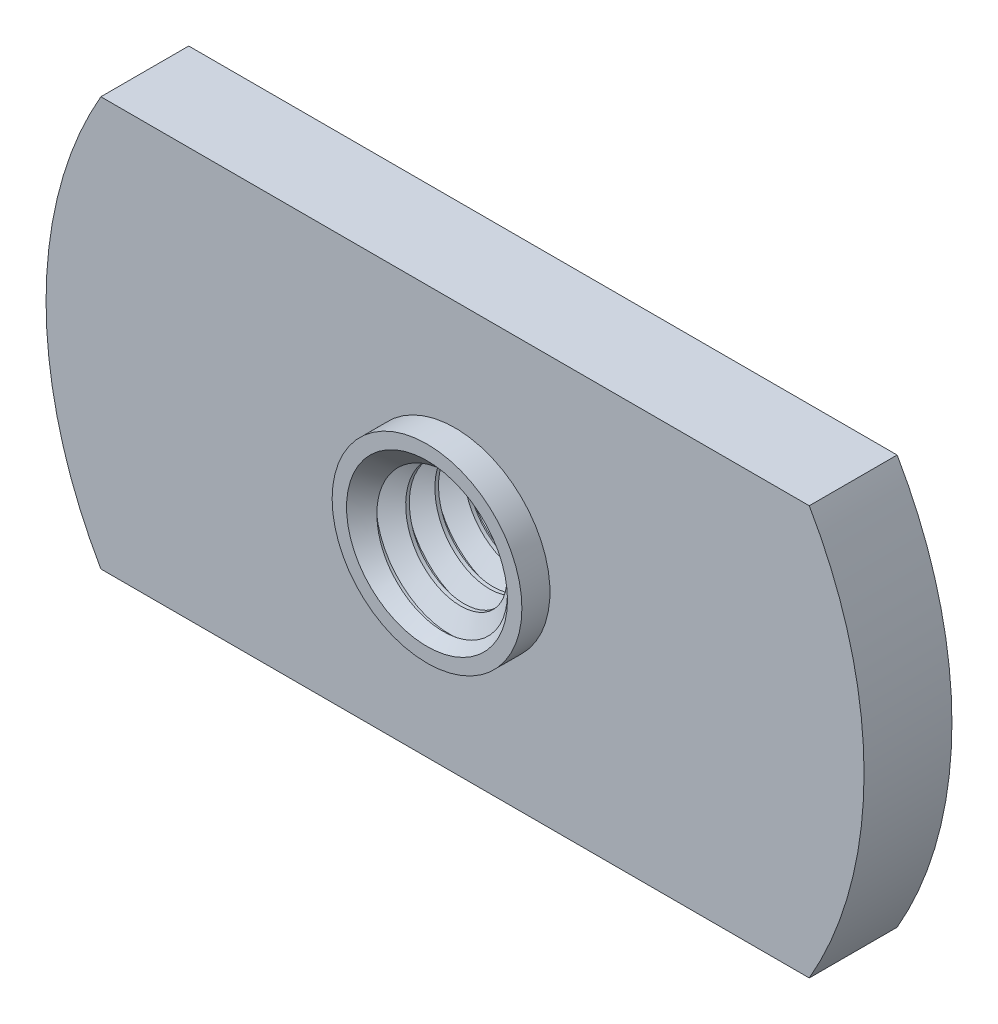
SolidWorks part; units mm, degrees
ref_plane "Front Plane" through (0, 0, 0) normal (0, 0, 1) x (1, 0, 0)
ref_plane "Top Plane" through (0, 0, 0) normal (0, 1, 0) x (1, 0, 0)
ref_plane "Right Plane" through (0, 0, 0) normal (1, 0, 0) x (0, 0, -1)
sketch "Sketch1" plane through (0, 0, 0) normal (0, 0, 1) x (1, 0, 0)
  line L0 (0, 5.5562) -> (0, -5.5562) construction
  line L1 (11.1125, 0) -> (-11.1125, 0) construction
  point P4 (0, 0)
  point P8 (0, 0)
  dimension "Length" = 22.225
  dimension "Width" = 11.1125
sketch "Sketch2" plane through (0, 0, 0) normal (1, 0, 0) x (0, 0, -1)
  line L0 (0, 0) -> (2.3876, 0) construction
  line L1 (0, 0) -> (-0.762, 0) construction
  line L2 (-0.762, 2.5781) -> (-0.762, -2.5781) construction
  line L3 (2.3876, 2.0828) -> (2.3876, -2.0828) construction
  line L5 (2.3876, -2.0828) -> (1.5939, -2.0828) construction
  line L6 (0, 5.5562) -> (0, -5.5562) construction
  point P7 (-0.762, 0)
  point P10 (2.3876, 0)
  dimension "E" = 5.1562
  dimension "Thread Dia" = 4.1656
  dimension "Pitch" = 0.7937
  dimension "B" = 2.3876
  dimension "F" = 0.762
sketch "Sketch3" plane through (0, 0, 0) normal (0, 0, 1) x (1, 0, 0)
  line L0 (9.6237, -5.5562) -> (-9.6237, -5.5562)
  line L4 (9.6237, 5.5562) -> (-9.6237, 5.5562)
  arc A2 (9.6237, 5.5562) -> (9.6237, -5.5562) centre (0, 0) cw
  arc A3 (-9.6237, 5.5562) -> (-9.6237, -5.5562) centre (0, 0) ccw
  circle A4 centre (0, 0) radius 2.0828
  point P3 (0, -2.0828)
  point P6 (-11.1125, 0)
extrude "Boss-Extrude1" add sketch "Sketch3" against normal up to vertex (2.3876 mm away) up to point (0, 0, -2.3876)
sketch "Sketch4" plane through (0, 0, 0) normal (0, 0, 1) x (1, 0, 0)
  circle A0 centre (0, 0) radius 2.0828 construction
  circle A1 centre (0, 0) radius 2.0828
  circle A2 centre (0, 0) radius 2.5781
  point P4 (0, 2.5781)
extrude "Boss-Extrude2" add sketch "Sketch4" along normal up to vertex (0.762 mm away) up to point (0, 0, 0.762)
sketch "Sketch5" plane through (0, 0, 0.762) normal (0, 0, 1) x (1, 0, 0)
  circle A0 centre (0, 0) radius 2.1869
  dimension "D1" = 4.3739
extrude "Cut-Extrude1" cut sketch "Sketch5" against normal through all draft 45
sketch "Sketch6" plane through (0, 0, 0.762) normal (0, 0, 1) x (1, 0, 0)
  circle A1 centre (0, 0) radius 2.0828
  circle A2 centre (0, 0) radius 2.0828 construction
extrude "Boss-Extrude3" add sketch "Sketch6" against normal up to surface (3.1496 mm away) separate body up to face at (2.0828, 0, -2.3876)
sketch "Sketch7" plane through (0, 0, 0.762) normal (0, 0, 1) x (1, 0, 0)
  circle A1 centre (0, 0) radius 2.0828
  circle A2 centre (0, 0) radius 2.0828
  dimension "D1" = 0
curve "Helix/Spiral1" pitch 0.7937 height 3.9434 turns 4.968
sketch "Sketch8" plane through (0, 0, 0) normal (1, 0, 0) x (0, 0, -1)
  line L0 (-1.5061, 2.1687) -> (-1.1093, 1.4813) construction
  line L1 (-1.1093, 1.4813) -> (-0.7124, 2.1687) construction
  line L2 (-0.7124, 2.1687) -> (-1.5061, 2.1687) construction
  line L3 (-1.1589, 1.5672) -> (-1.0597, 1.5672) construction
  line L4 (-1.4565, 2.0828) -> (-0.762, 2.0828) construction
  line L5 (-1.1093, 2.0828) -> (-1.1093, 2.1687) construction
  line L6 (-1.1093, 1.5672) -> (-1.1093, 1.4813) construction
  line L7 (-1.1093, 2.1258) -> (-1.4813, 2.1258) construction
  line L8 (-1.4813, 2.1258) -> (-0.7124, 2.1687)
  line L9 (-0.7124, 2.1687) -> (-1.0597, 1.5672)
  line L10 (-1.0597, 1.5672) -> (-1.1589, 1.5672)
  line L11 (-1.1589, 1.5672) -> (-1.4813, 2.1258)
  dimension "D1" = 0.7937
  dimension "D2" = 0.0992
sweep "Cut-Sweep1" cut profiles "Sketch8" path "Helix/Spiral1"
sketch "Sketch9" plane through (0, 0, 0.762) normal (0, 0, 1) x (1, 0, 0)
  circle A0 centre (0, 0) radius 2.1869
  dimension "D1" = 4.3739
extrude "Boss-Extrude4" add sketch "Sketch9" against normal blind 2.54 draft 45
sketch "Sketch10" plane through (0, 0, 0.762) normal (0, 0, 1) x (1, 0, 0)
  circle A0 centre (0, 0) radius 2.5781 construction
  circle A1 centre (0, 0) radius 2.5781
extrude "Boss-Extrude5" add sketch "Sketch10" against normal up to surface (3.1496 mm away) up to face at (2.0828, 0, -2.3876)
combine bodies "Combine1" operation type subtract main body 110 bodies to subtract 109
equation "\"D1@Sketch5\"=\"Thread Dia@Sketch2\"*1.05"
equation "\"D4@Helix/Spiral1\"=\"Pitch@Sketch2\""
equation "\"D3@Helix/Spiral1\"=\"Pitch@Sketch2\"+\"F@Sketch2\"+\"B@Sketch2\""
equation "\"D1@Sketch8\"=\"Pitch@Sketch2\""
equation "\"D2@Sketch8\"=\"Pitch@Sketch2\"/8"
equation "\"D1@Sketch9\"=\"Thread Dia@Sketch2\"*1.05"
